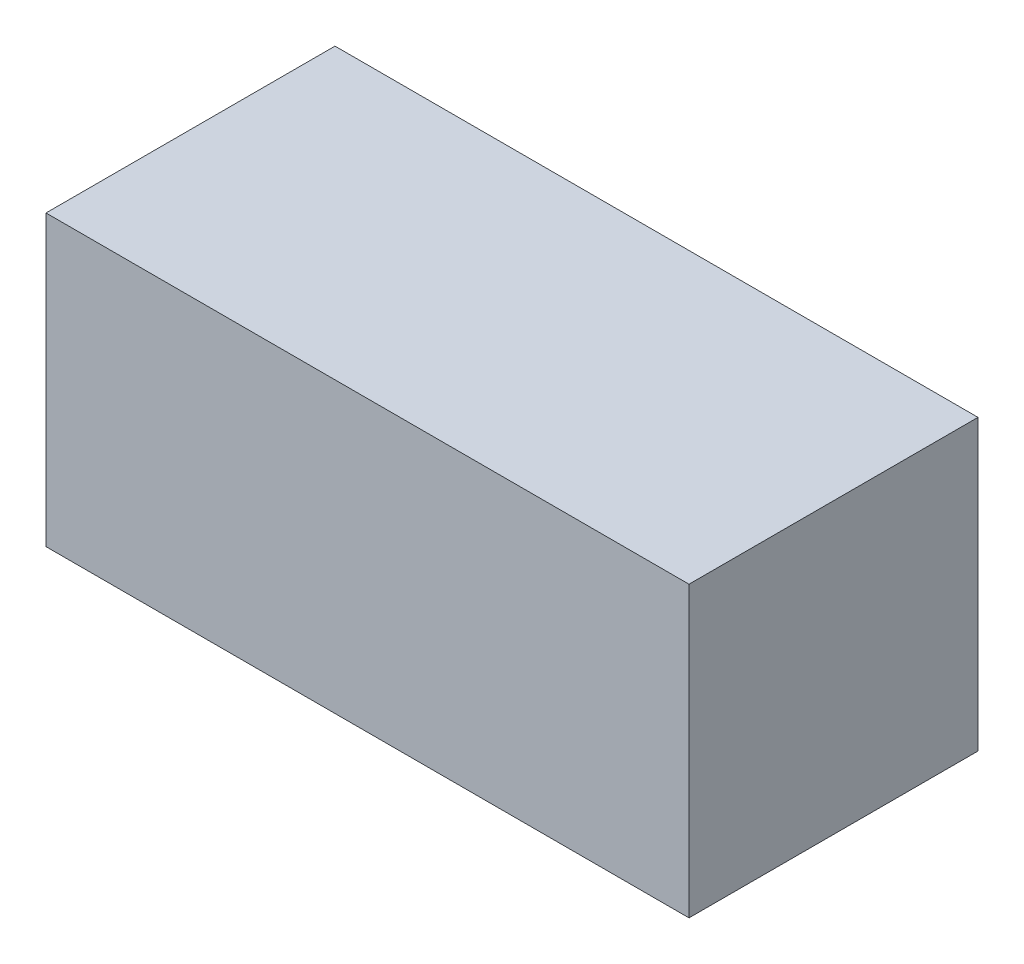
SolidWorks part; units mm, degrees
ref_plane "前视基准面" through (0, 0, 0) normal (0, 0, 1) x (1, 0, 0)
ref_plane "上视基准面" through (0, 0, 0) normal (0, 1, 0) x (1, 0, 0)
ref_plane "右视基准面" through (0, 0, 0) normal (1, 0, 0) x (0, 0, -1)
sketch "草图1" plane through (0, 0, 0) normal (0, 0, 1) x (1, 0, 0)
  line L0 (-1.1, -0.5) -> (-1.1, 0.5)
  line L1 (-1.1, 0.5) -> (1.125, 0.5)
  line L2 (1.125, 0.5) -> (1.125, -0.5)
  line L3 (1.125, -0.5) -> (-1.1, -0.5)
extrude "Component_Outline" add sketch "草图1" along normal blind 1 separate body
sketch3d "3D草图1"
  line L0 (0, 0, 0) -> (1, 0, 0)
  line L1 (0, 0, 0) -> (0, 1, 0)
  line L2 (0, 0, 0) -> (0, 0, 1)
  point P0 (0, 0, 0)
